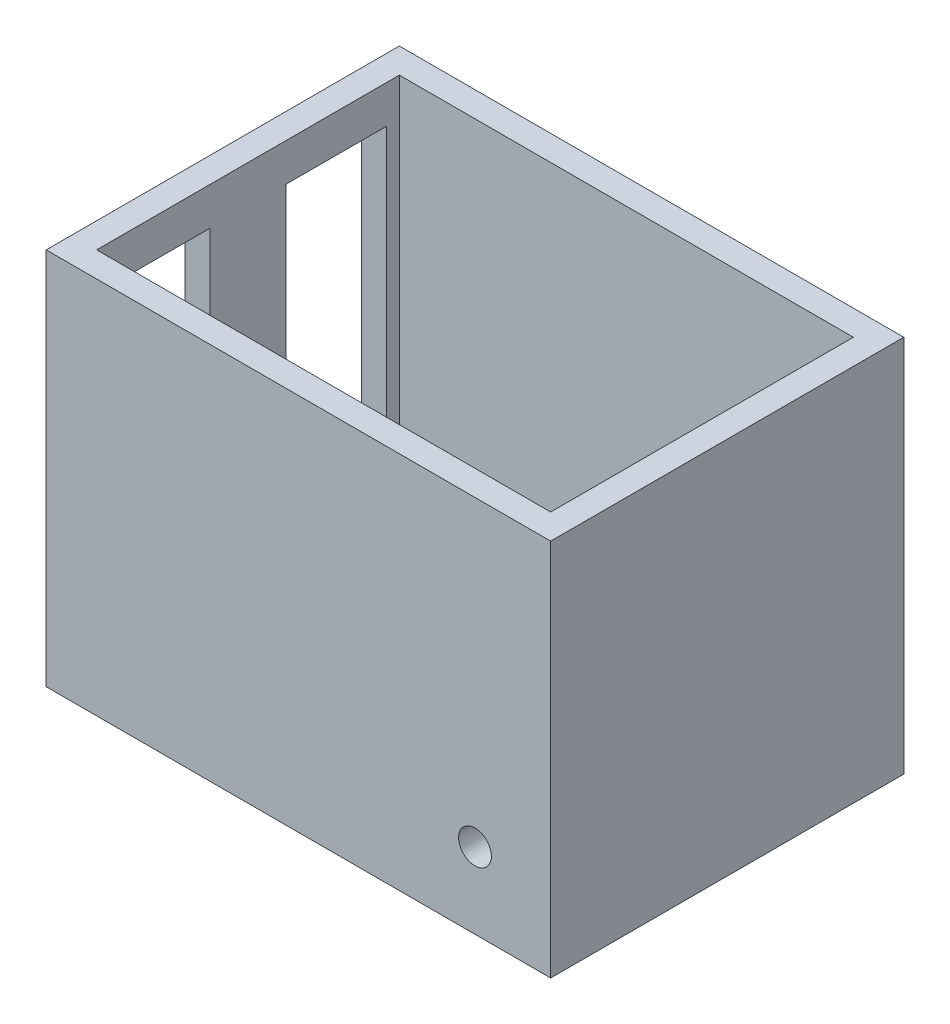
SolidWorks part; units mm, degrees
ref_plane "Front Plane" through (0, 0, 0) normal (0, 0, 1) x (1, 0, 0)
ref_plane "Top Plane" through (0, 0, 0) normal (0, 1, 0) x (1, 0, 0)
ref_plane "Right Plane" through (0, 0, 0) normal (1, 0, 0) x (0, 0, -1)
sketch "Sketch2" plane through (0, 0, 0) normal (0, 1, 0) x (1, 0, 0)
  line L1 (-44.7075, 29.2129) -> (56.8925, 29.2129)
  line L2 (-44.7075, 29.2129) -> (-44.7075, -41.9071)
  line L3 (-44.7075, -41.9071) -> (56.8925, -41.9071)
  line L4 (56.8925, 29.2129) -> (56.8925, -41.9071)
  dimension "D1" = 71.12
  dimension "D2" = 101.6
extrude "Boss-Extrude1" add sketch "Sketch2" along normal blind 76.2
sketch "Sketch3" plane through (0, 76.2, 0) normal (0, 1, 0) x (1, 0, 0)
  line L1 (-39.6275, 24.1329) -> (51.8125, 24.1329)
  line L2 (-39.6275, 24.1329) -> (-39.6275, -36.8271)
  line L3 (-39.6275, -36.8271) -> (51.8125, -36.8271)
  line L4 (51.8125, 24.1329) -> (51.8125, -36.8271)
  line L11 (56.8925, -41.9071) -> (56.8925, 29.2129) construction
  line L13 (-44.7075, -41.9071) -> (56.8925, -41.9071) construction
  dimension "D1" = 60.96
  dimension "D2" = 91.44
  dimension "D3" = 5.08
  dimension "D4" = 5.08
sketch "Sketch5" plane through (0, 0, 41.9071) normal (0, 0, 1) x (1, 0, 0)
  line L0 (56.8925, 76.2) -> (56.8925, 0) construction
  line L1 (-44.7075, 0) -> (56.8925, 0) construction
  circle A0 centre (41.6525, 15.24) radius 3.302
  dimension "D1" = 6.604
  dimension "D2" = 15.24
  dimension "D3" = 15.24
extrude "Cut-Extrude5" cut sketch "Sketch3" against normal blind 71.12 contours L1 L4 L3 L2
extrude "Cut-Extrude6" cut sketch "Sketch5" against normal blind 7.62 contours A0
sketch "Sketch7" plane through (0, 5.08, 0) normal (0, 1, 0) x (1, 0, 0)
  line L0 (-44.7075, 29.2129) -> (-44.7075, -41.9071) construction
  line L1 (-44.7075, -41.9071) -> (56.8925, -41.9071) construction
  line L2 (56.8925, 29.2129) -> (-44.7075, 29.2129) construction
  circle A0 centre (-12.9575, -3.8071) radius 5.08
  circle A1 centre (25.1425, -6.3471) radius 5.08
  dimension "D1" = 10.16
  dimension "D2" = 10.16
  dimension "D3" = 38.1
  dimension "D4" = 35.56
  dimension "D5" = 38.1
  dimension "D6" = 31.75
extrude "Cut-Extrude8" cut sketch "Sketch7" against normal blind 7.62
sketch "Sketch8" plane through (-44.7075, 0, 0) normal (-1, 0, 0) x (0, 0, 1)
  line L0 (-29.2129, 76.2) -> (-29.2129, 0) construction
  line L1 (-21.5929, 68.58) -> (-1.2729, 68.58)
  line L2 (-21.5929, 68.58) -> (-21.5929, 7.62)
  line L3 (-21.5929, 7.62) -> (-1.2729, 7.62)
  line L4 (-1.2729, 68.58) -> (-1.2729, 7.62)
  line L5 (13.9671, 68.58) -> (34.2871, 68.58)
  line L6 (13.9671, 68.58) -> (13.9671, 7.62)
  line L7 (13.9671, 7.62) -> (34.2871, 7.62)
  line L8 (34.2871, 68.58) -> (34.2871, 7.62)
  line L9 (-29.2129, 0) -> (41.9071, 0) construction
  line L10 (41.9071, 76.2) -> (41.9071, 0) construction
  point P8 (-29.2129, 38.1)
  dimension "D1" = 20.32
  dimension "D2" = 20.32
  dimension "D3" = 60.96
  dimension "D4" = 60.96
  dimension "D5" = 7.62
  dimension "D6" = 7.62
  dimension "D7" = 7.62
  dimension "D8" = 7.62
extrude "Cut-Extrude9" cut sketch "Sketch8" against normal blind 7.62
